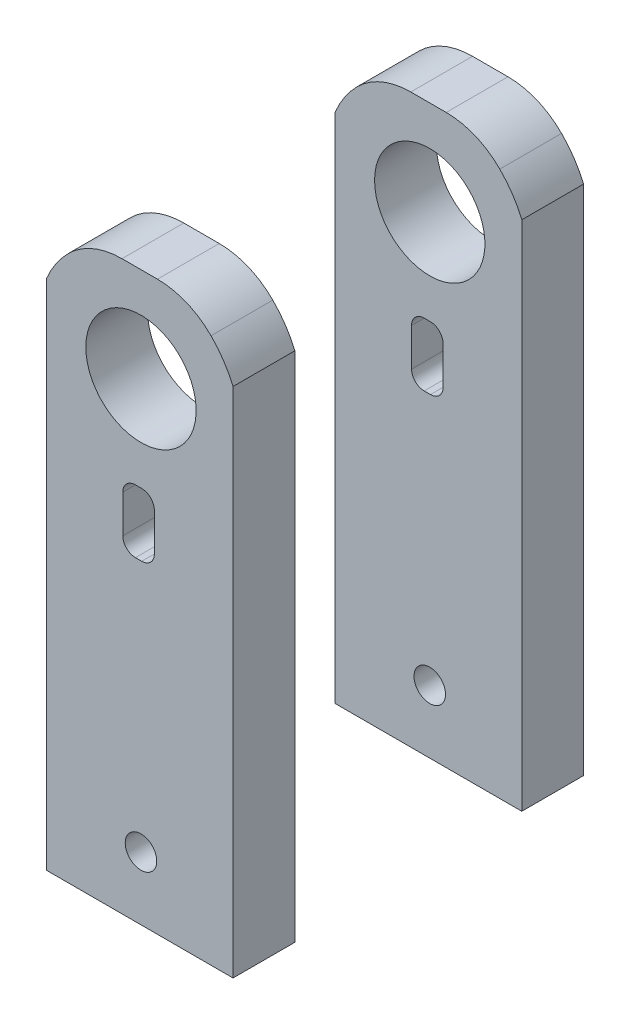
SolidWorks part; units mm, degrees
ref_plane "Front Plane" through (0, 0, 0) normal (0, 0, 1) x (1, 0, 0)
ref_plane "Top Plane" through (0, 0, 0) normal (0, 1, 0) x (1, 0, 0)
ref_plane "Right Plane" through (0, 0, 0) normal (1, 0, 0) x (0, 0, -1)
sketch "Sketch2" plane through (0, 0, 0) normal (0, 1, 0) x (1, 0, 0)
  line L0 (-19.05, 6.223) -> (18.542, 6.223)
  line L1 (0, 0) -> (12.6901, 0) construction
  line L2 (-19.05, -6.223) -> (18.542, -6.223)
  line L3 (-19.05, 6.223) -> (-19.05, -6.223)
  line L4 (18.542, 6.223) -> (18.542, -6.223)
  point P3 (-0.254, 6.223)
  dimension "D1" = 37.592
  dimension "D2" = 6.223
  dimension "D3" = 12.446
extrude "Boss-Extrude1" add sketch "Sketch2" along normal blind 114.3
ref_plane "Plane1" through (0, 0, 29.083) normal (0, 0, 1) x (1, 0, 0)
sketch "Sketch3" plane through (0, 0, -6.223) normal (0, 0, -1) x (-1, 0, 0)
  circle A0 centre (0, 12.7) radius 3.175
  dimension "D1" = 12.7
sketch "Sketch4" plane through (0, 0, -6.223) normal (0, 0, -1) x (-1, 0, 0)
  circle A0 centre (0, 95.25) radius 11.1125
  dimension "D1" = 95.25
  dimension "D2" = 22.225
extrude "Cut-Extrude1" cut sketch "Sketch3" against normal blind 12.7
extrude "Cut-Extrude2" cut sketch "Sketch4" against normal blind 12.7
sketch "Sketch5" plane through (0, 0, -6.223) normal (0, 0, -1) x (-1, 0, 0)
  line L0 (-2.6881, 76.2) -> (-2.6881, 63.5)
  line L1 (-2.6881, 76.2) -> (3.6619, 76.2)
  line L2 (-2.6881, 63.5) -> (3.6619, 63.5)
  line L3 (3.6619, 76.2) -> (3.6619, 63.5)
  line L4 (-2.6881, 76.2) -> (3.6619, 63.5) construction
  line L5 (-2.6881, 63.5) -> (3.6619, 76.2) construction
  line L6 (0.254, 0) -> (11.2164, 0) construction
  line L7 (-18.542, 0) -> (19.05, 0) construction
  point P1 (0.4869, 69.85)
  dimension "D1" = 12.7
  dimension "D2" = 6.35
  dimension "D3" = 63.5
extrude "Cut-Extrude3" cut sketch "Sketch5" against normal blind 12.7
mirror "Mirror7" about plane through (0, 0, 29.083) normal (0, 0, 1) of bodies 104
fillet "Fillet2" radius 2.54 4 edges at (2.6881, 76.2, 0) (-3.6619, 76.2, 0) (2.6881, 63.5, 0) (-3.6619, 63.5, 0)
fillet "Fillet3" radius 2.54 4 edges at (2.6881, 63.5, 58.166) (2.6881, 76.2, 58.166) (-3.6619, 76.2, 58.166) (-3.6619, 63.5, 58.166)
sketch "Sketch6" plane through (0, 0, 64.389) normal (0, 0, 1) x (1, 0, 0)
  line L4 (-19.05, 114.3) -> (-19.05, 103.1875)
  line L5 (-19.05, 114.3) -> (-19.05, 0) construction
  line L6 (-19.05, 114.3) -> (-7.9375, 114.3)
  line L7 (18.542, 114.3) -> (-19.05, 114.3) construction
  line L9 (-0.254, 114.3) -> (-0.254, 109.4006) construction
  line L10 (18.542, 114.3) -> (7.4295, 114.3)
  line L11 (18.542, 114.3) -> (18.542, 103.1875)
  arc A0 (-7.9375, 114.3) -> (-19.05, 103.1875) centre (0, 95.25) ccw
  arc A1 (7.4295, 114.3) -> (18.542, 103.1875) centre (-0.508, 95.25) cw
extrude "Cut-Extrude4" cut sketch "Sketch6" against normal up to surface (70.612 mm away)
fillet "Fillet4" radius 15.24 2 edges at (7.4295, 114.3, 0) (-7.9375, 114.3, 0)
fillet "Fillet5" radius 15.24 2 edges at (-7.9375, 114.3, 58.166) (7.4295, 114.3, 58.166)
